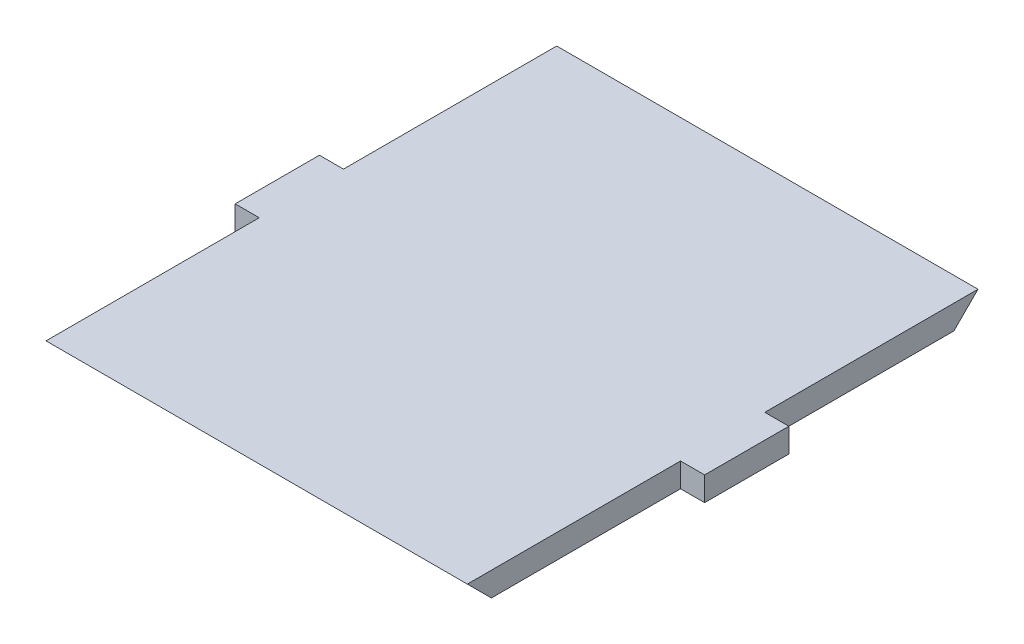
SolidWorks part; units mm, degrees
ref_plane "Front Plane" through (0, 0, 0) normal (0, 0, 1) x (1, 0, 0)
ref_plane "Top Plane" through (0, 0, 0) normal (0, 1, 0) x (1, 0, 0)
ref_plane "Right Plane" through (0, 0, 0) normal (1, 0, 0) x (0, 0, -1)
sketch "Sketch1" plane through (0, 0, 0) normal (0, 1, 0) x (1, 0, 0)
  line L1 (-6.4003, 21.8091) -> (28.5997, 21.8091)
  line L2 (-6.4003, 21.8091) -> (-6.4003, -20.6173)
  line L3 (-6.4003, -20.6173) -> (28.5997, -20.6173)
  line L4 (28.5997, 21.8091) -> (28.5997, -20.6173)
  line L5 (-6.4003, 4.0977) -> (-8.4003, 4.0977)
  line L6 (-6.4003, 4.0977) -> (-6.4003, -2.9023)
  line L7 (-6.4003, -2.9023) -> (-8.4003, -2.9023)
  line L8 (-8.4003, 4.0977) -> (-8.4003, -2.9023)
  line L9 (28.5997, 4.0977) -> (30.5997, 4.0977)
  line L10 (28.5997, 4.0977) -> (28.5997, -2.9023)
  line L11 (28.5997, -2.9023) -> (30.5997, -2.9023)
  line L12 (30.5997, 4.0977) -> (30.5997, -2.9023)
  dimension "D1" = 2
  dimension "D2" = 2
  dimension "D3" = 35
  dimension "D4" = 42.4264
  dimension "D5" = 7
  dimension "D6" = 7
  dimension "D7" = 17.715
  dimension "D8" = 17.7114
  dimension "D9" = 17.715
  dimension "D10" = 17.7114
extrude "Boss-Extrude1" add sketch "Sketch1" along normal blind 2 contours L5 L8 L7 L2 | L4 L1 L2 L3 | L12 L9 L4 L11
sketch "Sketch2" plane through (28.5997, 0, 0) normal (1, 0, 0) x (0, 0, -1)
  line L0 (-20.6173, 2) -> (-18.6173, 0)
  line L1 (-2.9023, 0) -> (-20.6173, 0) construction
  line L2 (-18.6173, 0) -> (-20.6173, 0)
  line L3 (-20.6173, 0) -> (-20.6173, 2)
  line L4 (21.8091, 2) -> (21.8091, 0)
  line L5 (21.8091, 0) -> (19.8091, 0)
  line L6 (21.8091, 0) -> (4.0977, 0) construction
  line L7 (19.8091, 0) -> (21.8091, 2)
  dimension "D1" = 45
  dimension "D2" = 45
extrude "Cut-Extrude1" cut sketch "Sketch2" against normal through all
